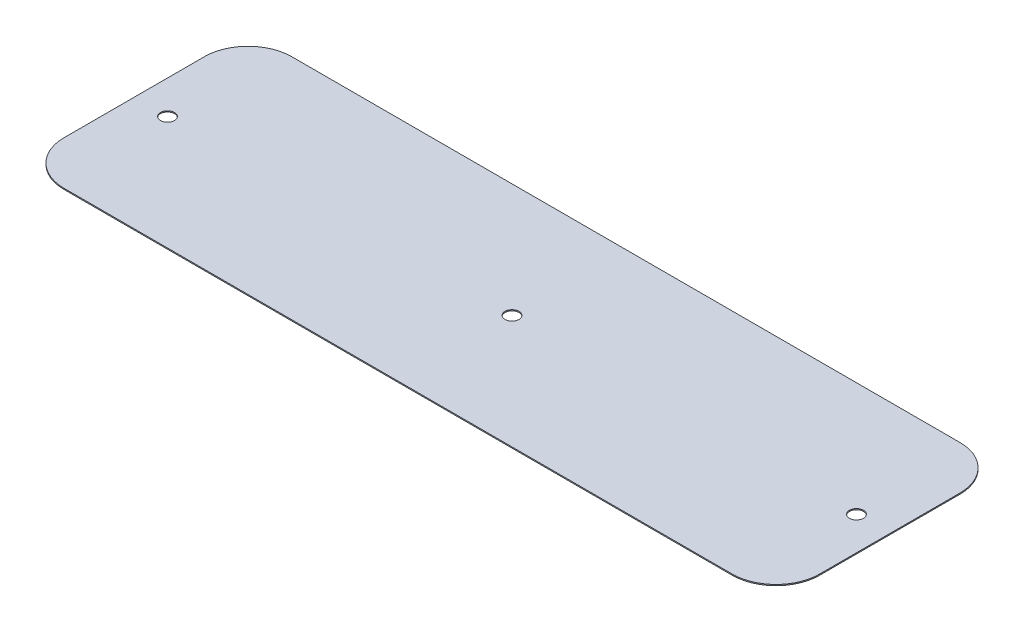
SolidWorks part; units mm, degrees
material "6061 Alloy"
ref_plane "Front" through (0, 0, 0) normal (0, 0, 1) x (1, 0, 0)
ref_plane "Top" through (0, 0, 0) normal (0, 1, 0) x (1, 0, 0)
ref_plane "Right" through (0, 0, 0) normal (1, 0, 0) x (0, 0, -1)
sketch "Sketch1" plane through (0, 0, 0) normal (0, 1, 0) x (1, 0, 0)
  line L1 (-86.36, -26.035) -> (86.36, -26.035)
  line L2 (-86.36, -26.035) -> (-86.36, 26.035)
  line L3 (-86.36, 26.035) -> (86.36, 26.035)
  line L4 (86.36, -26.035) -> (86.36, 26.035)
  line L5 (-86.36, -26.035) -> (86.36, 26.035) construction
  line L6 (-86.36, 26.035) -> (86.36, -26.035) construction
  point P0 (0, 0)
  dimension "D1" = 172.72
  dimension "D2" = 52.07
extrude "Boss-Extrude1" add sketch "Sketch1" along normal blind 0.25
fillet "Fillet1" radius 10 4 edges at (-86.36, 0.125, -26.035) (86.36, 0.125, -26.035) (86.36, 0.125, 26.035) (-86.36, 0.125, 26.035)
sketch "Sketch2" plane through (0, 0.25, 0) normal (0, 1, 0) x (1, 0, 0)
  circle A0 centre (-78.74, 0) radius 1.6
  circle A1 centre (0, 0) radius 1.6
  point P5 (0, 0)
  dimension "D1" = 3.2
  dimension "D2" = 78.74
extrude "Cut-Extrude1" cut sketch "Sketch2" against normal through all
mirror "Mirror1" about plane through (0, 0, 0) normal (1, 0, 0) of "Cut-Extrude1"
